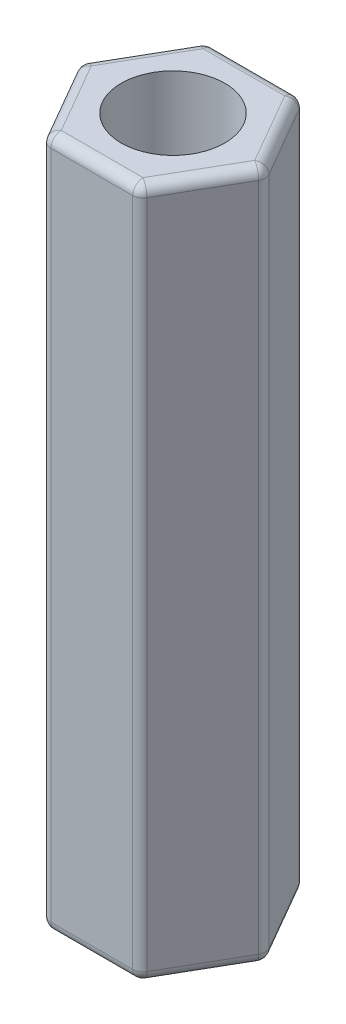
SolidWorks part; units mm, degrees
ref_plane "前视基准面" through (0, 0, 0) normal (0, 0, 1) x (1, 0, 0)
ref_plane "上视基准面" through (0, 0, 0) normal (0, 1, 0) x (1, 0, 0)
ref_plane "右视基准面" through (0, 0, 0) normal (1, 0, 0) x (0, 0, -1)
sketch "草图1" plane through (0, 0, 0) normal (0, 1, 0) x (1, 0, 0)
  line L1 (2.7135, 0) -> (1.3568, 2.35)
  line L2 (1.3568, 2.35) -> (-1.3568, 2.35)
  line L3 (-1.3568, 2.35) -> (-2.7135, 0)
  line L4 (-2.7135, 0) -> (-1.3568, -2.35)
  line L5 (-1.3568, -2.35) -> (1.3568, -2.35)
  line L6 (1.3568, -2.35) -> (2.7135, 0)
  circle A0 centre (0, 0) radius 2.35 construction
  circle A1 centre (0, 0) radius 1.5
  dimension "D1" = 4.7
extrude "凸台-拉伸1" add sketch "草图1" along normal blind 20
fillet "圆角1" radius 0.3 18 edges at (2.7135, 10, 0) (1.3568, 10, -2.35) (-1.3568, 10, -2.35) (-2.7135, 10, 0) (-1.3568, 10, 2.35) (1.3568, 10, 2.35) (0, 20, 2.35) (-2.0352, 20, 1.175) (-2.0352, 20, -1.175) (0, 20, -2.35) (2.0352, 20, -1.175) (2.0352, 20, 1.175) (0, 0, 2.35) (-2.0352, 0, 1.175) (-2.0352, 0, -1.175) (0, 0, -2.35) (2.0352, 0, -1.175) (2.0352, 0, 1.175)
